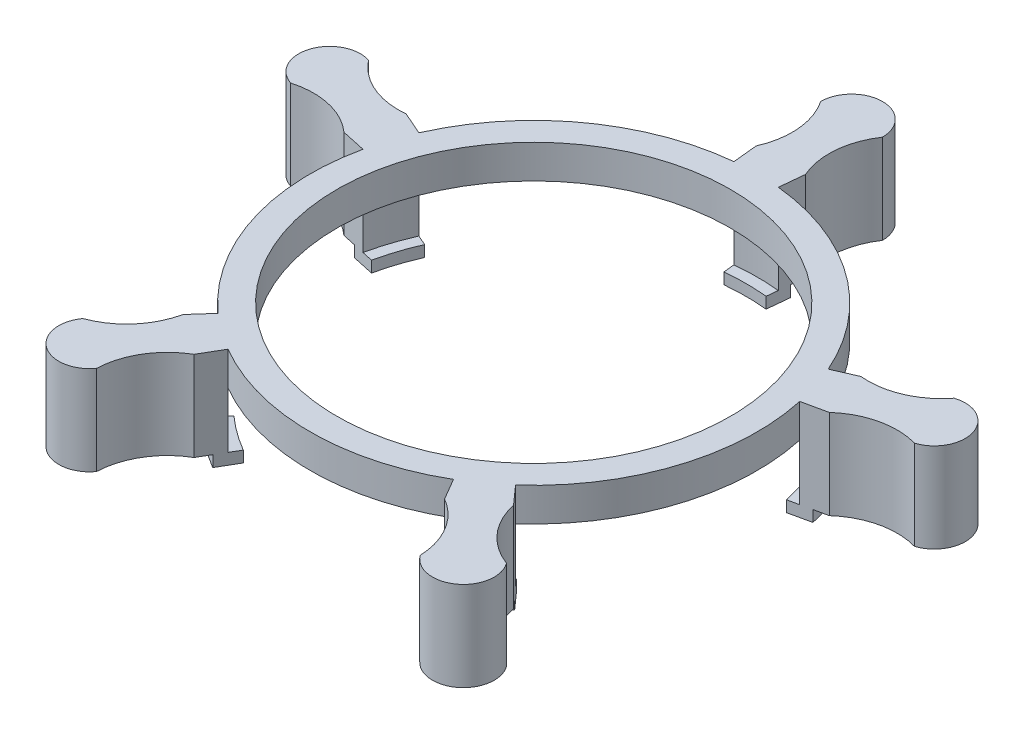
SolidWorks part; units mm, degrees
ref_plane "Front Plane" through (0, 0, 0) normal (0, 0, 1) x (1, 0, 0)
ref_plane "Top Plane" through (0, 0, 0) normal (0, 1, 0) x (1, 0, 0)
ref_plane "Right Plane" through (0, 0, 0) normal (1, 0, 0) x (0, 0, -1)
sketch "Sketch1" plane through (0, 0, 0) normal (0, 1, 0) x (1, 0, 0)
  circle A0 centre (0, 0) radius 55.88
  circle A1 centre (0, 0) radius 63.5
extrude "Boss-Extrude3" add sketch "Sketch1" against normal blind 9.525
sketch "Sketch5" plane through (0, 0, 0) normal (0, 1, 0) x (1, 0, 0)
  circle A0 centre (0, 0) radius 63.5 construction
  arc A1 (-8.775, 90.3187) -> (8.775, 90.3187) centre (0, 90.3187) cw
  arc A2 (8.775, 90.3187) -> (13.3993, 62.0702) centre (26.1497, 78.6602) ccw
  arc A3 (-8.775, 90.3187) -> (-13.3993, 62.0702) centre (-26.1497, 78.6602) cw
  arc A4 (13.3993, 62.0702) -> (-13.3993, 62.0702) centre (0, 0) ccw
  arc A5 (63.1729, 6.4372) -> (54.8916, 31.9243) centre (0, 0) ccw
  arc A6 (83.1866, 36.2555) -> (54.8916, 31.9243) centre (66.7296, 49.1772) cw
  arc A7 (83.1866, 36.2555) -> (88.6098, 19.5645) centre (85.8982, 27.91) cw
  arc A8 (88.6098, 19.5645) -> (63.1729, 6.4372) centre (82.891, -0.5625) ccw
  arc A9 (25.6437, -58.0918) -> (47.3242, -42.3399) centre (0, 0) ccw
  arc A10 (60.1871, -67.9116) -> (47.3242, -42.3399) centre (67.3909, -48.2671) cw
  arc A11 (60.1871, -67.9116) -> (45.9889, -78.2272) centre (53.088, -73.0694) cw
  arc A12 (45.9889, -78.2272) -> (25.6437, -58.0918) centre (25.0798, -79.0079) ccw
  arc A13 (-47.3242, -42.3399) -> (-25.6437, -58.0918) centre (0, 0) ccw
  arc A14 (-45.9889, -78.2272) -> (-25.6437, -58.0918) centre (-25.0798, -79.0079) cw
  arc A15 (-45.9889, -78.2272) -> (-60.1871, -67.9116) centre (-53.088, -73.0694) cw
  arc A16 (-60.1871, -67.9116) -> (-47.3242, -42.3399) centre (-67.3909, -48.2671) ccw
  arc A17 (-54.8916, 31.9243) -> (-63.1729, 6.4372) centre (0, 0) ccw
  arc A18 (-88.6098, 19.5645) -> (-63.1729, 6.4372) centre (-82.891, -0.5625) cw
  arc A19 (-88.6098, 19.5645) -> (-83.1866, 36.2555) centre (-85.8982, 27.91) cw
  arc A20 (-83.1866, 36.2555) -> (-54.8916, 31.9243) centre (-66.7296, 49.1772) ccw
  point P43 (0, 0)
  dimension "D1" = 5
extrude "Boss-Extrude5" add sketch "Sketch5" against normal blind 25.4
sketch "Sketch6" plane through (0, -9.525, 0) normal (0, -1, 0) x (-1, 0, 0)
  line L0 (54.8916, 31.9243) -> (57.6362, 33.5205)
  line L1 (63.1729, 6.4372) -> (66.3479, 6.4372)
  arc A0 (63.1729, 6.4372) -> (54.8916, 31.9243) centre (0, 0) ccw
  arc A1 (66.3479, 6.4372) -> (57.6228, 33.5126) centre (0, 0) ccw
extrude "Boss-Extrude7" add sketch "Sketch6" along normal blind 19.05 separate body
combine bodies "Combine1" operation type add bodies to combine 105 107
pattern_circular "CirPattern3" count 5 over 360 about axis through (0, 0, 0) along (0, 1, 0) of bodies 109
sketch "Sketch8" plane through (0, -28.575, 0) normal (0, -1, 0) x (-1, 0, 0)
  line L0 (72.378, 31.7745) -> (56.8729, 38.8206)
  line L1 (56.8729, 38.8206) -> (52.4467, 35.7993)
  line L2 (77.2316, 16.8366) -> (69.1031, 0)
  line L3 (69.1031, 0) -> (63.4966, 0.654)
  line L4 (62.0428, 13.5254) -> (77.2316, 16.8366)
  line L5 (42.2437, -47.4101) -> (52.5854, -59.0167)
  line L6 (52.5854, -59.0167) -> (54.4953, -42.0932)
  line L7 (54.4953, -42.0932) -> (50.2541, -38.8172)
  line L8 (32.0357, -54.8267) -> (39.8784, -68.2489)
  line L9 (39.8784, -68.2489) -> (21.354, -65.7209)
  line L10 (21.354, -65.7209) -> (20.2436, -60.1868)
  line L11 (-32.0357, -54.8267) -> (-39.8784, -68.2489)
  line L12 (58.1437, 25.5256) -> (72.378, 31.7745)
  line L13 (-39.8784, -68.2489) -> (-23.193, -64.8356)
  line L14 (-23.193, -64.8356) -> (-21.388, -59.7897)
  line L15 (-42.2437, -47.4101) -> (-52.5854, -59.0167)
  line L16 (-52.5854, -59.0167) -> (-55.9056, -40.6178)
  line L17 (-55.9056, -40.6178) -> (-50.9854, -37.8515)
  line L18 (-62.0428, 13.5254) -> (-77.2316, 16.8366)
  line L19 (-77.2316, 16.8366) -> (-68.8294, 2.0225)
  line L20 (-68.8294, 2.0225) -> (-63.4726, 1.8651)
  line L21 (-58.1437, 25.5256) -> (-72.378, 31.7745)
  line L22 (-72.378, 31.7745) -> (-55.9056, 40.6178)
  line L23 (-55.9056, 40.6178) -> (-51.7543, 36.7933)
  line L24 (-6.3089, 63.1858) -> (-7.8534, 78.6544)
  line L25 (-7.8534, 78.6544) -> (-19.3459, 66.0856)
  line L26 (-19.3459, 66.0856) -> (-17.8403, 60.9424)
  line L27 (6.3089, 63.1858) -> (7.8534, 78.6544)
  line L28 (7.8534, 78.6544) -> (21.354, 65.7209)
  line L29 (21.354, 65.7209) -> (18.9995, 60.591)
  arc A0 (63.4966, 0.654) -> (62.0428, 13.5254) centre (0, 0) ccw
  arc A1 (58.1437, 25.5256) -> (52.4467, 35.7993) centre (0, 0) ccw
  arc A2 (42.2437, -47.4101) -> (50.2541, -38.8172) centre (0, 0) ccw
  arc A3 (20.2436, -60.1868) -> (32.0357, -54.8267) centre (0, 0) ccw
  arc A4 (-32.0357, -54.8267) -> (-21.388, -59.7897) centre (0, 0) ccw
  arc A5 (-50.9854, -37.8515) -> (-42.2437, -47.4101) centre (0, 0) ccw
  arc A6 (-62.0428, 13.5254) -> (-63.4726, 1.8651) centre (0, 0) ccw
  arc A7 (-51.7543, 36.7933) -> (-58.1437, 25.5256) centre (0, 0) ccw
  arc A8 (-6.3089, 63.1858) -> (-17.8403, 60.9424) centre (0, 0) ccw
  arc A9 (18.9995, 60.591) -> (6.3089, 63.1858) centre (0, 0) ccw
  point P50 (0, 0)
  dimension "D1" = 5
extrude "Cut-Extrude2" cut sketch "Sketch8" against normal blind 50.8
sketch "Sketch9" plane through (0, -28.575, 0) normal (0, -1, 0) x (-1, 0, 0)
  line L0 (58.1437, 25.5256) -> (55.2365, 24.2493)
  line L1 (58.9407, 12.8491) -> (62.0428, 13.5254)
  arc A0 (62.0428, 13.5254) -> (58.1437, 25.5256) centre (0, 0) ccw
  arc A1 (58.9407, 12.8491) -> (55.2365, 24.2493) centre (0, 0) ccw
extrude "Boss-Extrude8" add sketch "Sketch9" against normal blind 3.175
pattern_circular "CirPattern5" count 5 over 360 about axis through (0, -9.525, 0) along (0, 1, 0) of "Boss-Extrude8"
